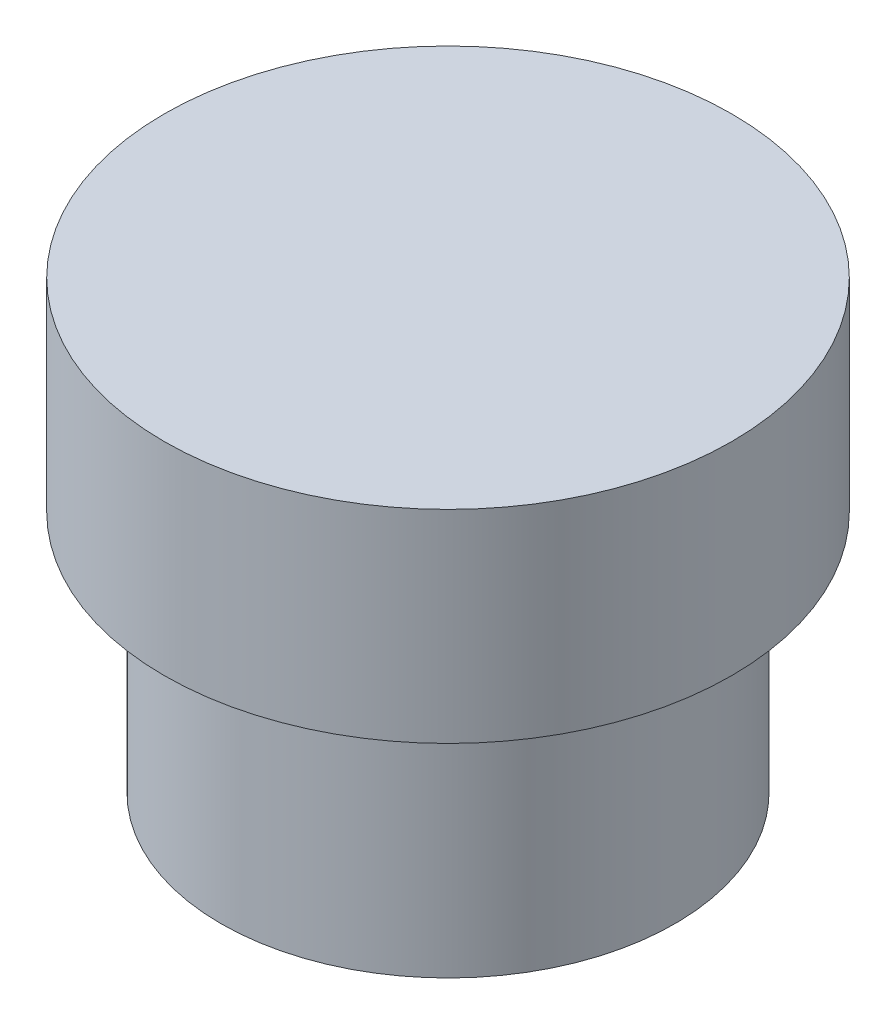
SolidWorks part; units mm, degrees
ref_plane "Front Plane" through (0, 0, 0) normal (0, 0, 1) x (1, 0, 0)
ref_plane "Top Plane" through (0, 0, 0) normal (0, 1, 0) x (1, 0, 0)
ref_plane "Right Plane" through (0, 0, 0) normal (1, 0, 0) x (0, 0, -1)
sketch "Sketch2" plane through (0, 0, 0) normal (0, 0, 1) x (1, 0, 0)
  line L0 (0, 56.5548) -> (0, 0) construction
  line L1 (0, 0) -> (5.6, 0)
  line L2 (5.6, 0) -> (5.6, 6)
  line L3 (5.6, 6) -> (7, 6)
  line L4 (7, 6) -> (7, 11)
  line L5 (7, 11) -> (0, 11)
  line L6 (0, 11) -> (0, 0)
  dimension "D1" = 14
  dimension "D2" = 11.2
  dimension "D3" = 5
  dimension "D4" = 11
revolve "Revolve1" add sketch "Sketch2" angle 360 about L0
